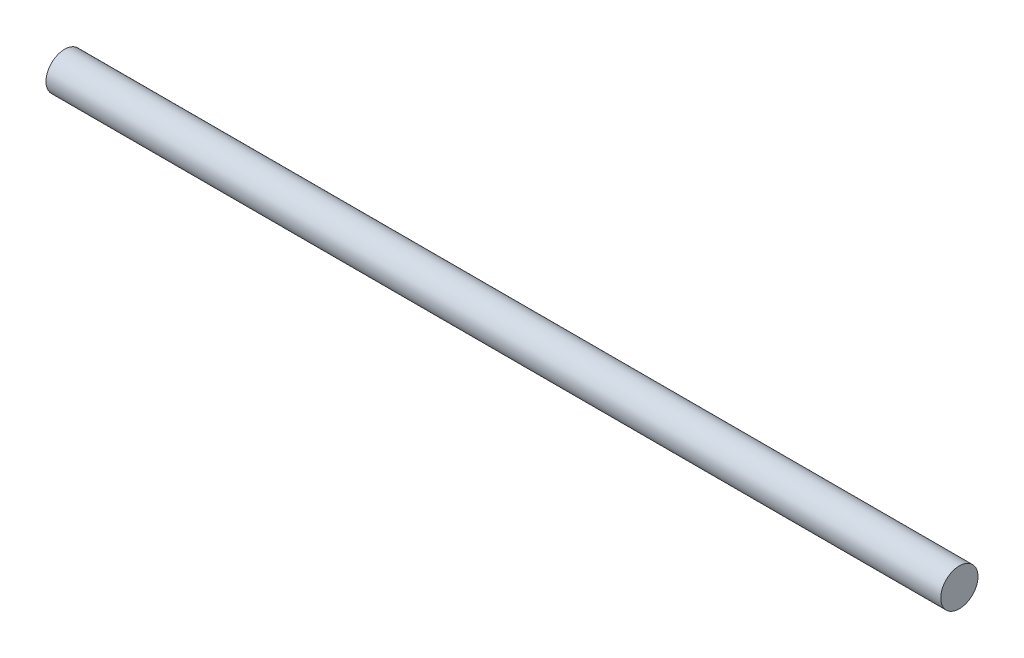
SolidWorks part; units mm, degrees
ref_plane "Front Plane" through (0, 0, 0) normal (0, 0, 1) x (1, 0, 0)
ref_plane "Top Plane" through (0, 0, 0) normal (0, 1, 0) x (1, 0, 0)
ref_plane "Right Plane" through (0, 0, 0) normal (1, 0, 0) x (0, 0, -1)
sketch "Sketch1" plane through (0, 0, 0) normal (1, 0, 0) x (0, 0, -1)
  circle A0 centre (0, 0) radius 2.5
  dimension "D1" = 5
extrude "Boss-Extrude1" add sketch "Sketch1" along normal blind 120
